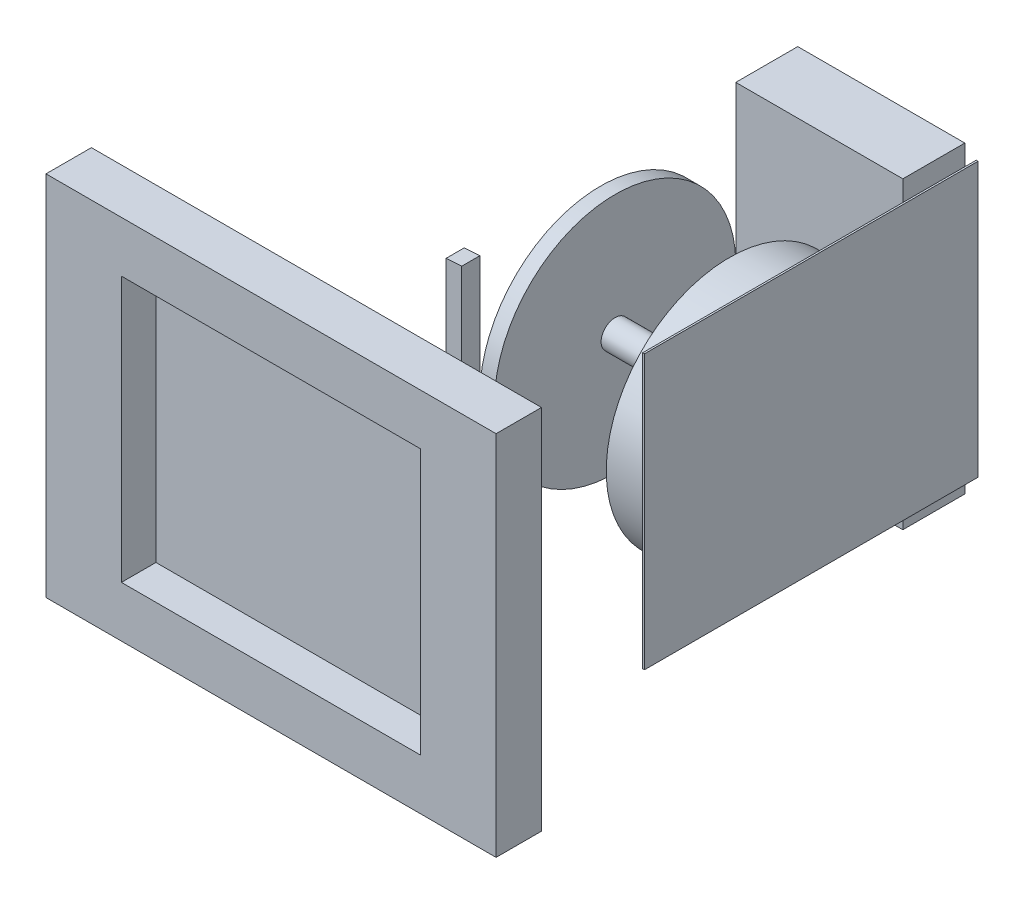
SolidWorks part; units mm, degrees
ref_plane "前视基准面" through (0, 0, 0) normal (0, 0, 1) x (1, 0, 0)
ref_plane "上视基准面" through (0, 0, 0) normal (0, 1, 0) x (1, 0, 0)
ref_plane "右视基准面" through (0, 0, 0) normal (1, 0, 0) x (0, 0, -1)
sketch "草图1" plane through (0, 0, 0) normal (1, 0, 0) x (0, 0, -1)
  circle A0 centre (0, 0) radius 66.4633
extrude "凸台-拉伸1" add sketch "草图1" along normal blind 5
sketch "草图2" plane through (5, 0, 0) normal (1, 0, 0) x (0, 0, -1)
  circle A3 centre (0, 36) radius 4.5304
  circle A6 centre (0, 15) radius 3.9065
  circle A7 centre (0, 0) radius 5.4141
  circle A8 centre (0, 58.5926) radius 4
  circle A9 centre (14.5714, 56.7518) radius 4
  circle A10 centre (28.2272, 51.3451) radius 4
  circle A11 centre (40.1094, 42.7122) radius 4
  circle A12 centre (49.4714, 31.3955) radius 4
  circle A13 centre (55.7249, 18.1061) radius 4
  circle A14 centre (58.477, 3.6791) radius 4
  circle A15 centre (57.5548, -10.9792) radius 4
  circle A16 centre (53.0162, -24.9475) radius 4
  circle A17 centre (45.1464, -37.3483) radius 4
  circle A18 centre (34.4399, -47.4024) radius 4
  circle A19 centre (21.5694, -54.478) radius 4
  circle A20 centre (7.3436, -58.1306) radius 4
  circle A21 centre (-7.3436, -58.1306) radius 4
  circle A22 centre (-21.5694, -54.478) radius 4
  circle A23 centre (-34.4399, -47.4024) radius 4
  circle A24 centre (-45.1464, -37.3483) radius 4
  circle A25 centre (-53.0162, -24.9475) radius 4
  circle A26 centre (-57.5548, -10.9792) radius 4
  circle A27 centre (-58.477, 3.6791) radius 4
  circle A28 centre (-55.7249, 18.1061) radius 4
  circle A29 centre (-49.4714, 31.3955) radius 4
  circle A30 centre (-40.1094, 42.7122) radius 4
  circle A31 centre (-28.2272, 51.3451) radius 4
  circle A32 centre (-14.5714, 56.7518) radius 4
  circle A33 centre (0, 48) radius 4.1999
  circle A34 centre (14.8328, 45.6507) radius 4.1999
  circle A35 centre (28.2137, 38.8328) radius 4.1999
  circle A36 centre (38.8328, 28.2137) radius 4.1999
  circle A37 centre (45.6507, 14.8328) radius 4.1999
  circle A38 centre (48, 0) radius 4.1999
  circle A39 centre (45.6507, -14.8328) radius 4.1999
  circle A40 centre (38.8328, -28.2137) radius 4.1999
  circle A41 centre (28.2137, -38.8328) radius 4.1999
  circle A42 centre (14.8328, -45.6507) radius 4.1999
  circle A43 centre (0, -48) radius 4.1999
  circle A44 centre (-14.8328, -45.6507) radius 4.1999
  circle A45 centre (-28.2137, -38.8328) radius 4.1999
  circle A46 centre (-38.8328, -28.2137) radius 4.1999
  circle A47 centre (-45.6507, -14.8328) radius 4.1999
  circle A48 centre (-48, 0) radius 4.1999
  circle A49 centre (-45.6507, 14.8328) radius 4.1999
  circle A50 centre (-38.8328, 28.2137) radius 4.1999
  circle A51 centre (-28.2137, 38.8328) radius 4.1999
  circle A52 centre (-14.8328, 45.6507) radius 4.1999
  circle A53 centre (12.3127, 33.8289) radius 4.5304
  circle A54 centre (23.1404, 27.5776) radius 4.5304
  circle A55 centre (31.1769, 18) radius 4.5304
  circle A56 centre (35.4531, 6.2513) radius 4.5304
  circle A57 centre (35.4531, -6.2513) radius 4.5304
  circle A58 centre (31.1769, -18) radius 4.5304
  circle A59 centre (23.1404, -27.5776) radius 4.5304
  circle A60 centre (12.3127, -33.8289) radius 4.5304
  circle A61 centre (0, -36) radius 4.5304
  circle A62 centre (-12.3127, -33.8289) radius 4.5304
  circle A63 centre (-23.1404, -27.5776) radius 4.5304
  circle A64 centre (-31.1769, -18) radius 4.5304
  circle A65 centre (-35.4531, -6.2513) radius 4.5304
  circle A66 centre (-35.4531, 6.2513) radius 4.5304
  circle A67 centre (-31.1769, 18) radius 4.5304
  circle A68 centre (-23.1404, 27.5776) radius 4.5304
  circle A69 centre (-12.3127, 33.8289) radius 4.5304
  circle A70 centre (0, 25) radius 4.3126
  circle A71 centre (12.5, 21.6506) radius 4.3126
  circle A72 centre (21.6506, 12.5) radius 4.3126
  circle A73 centre (25, 0) radius 4.3126
  circle A74 centre (21.6506, -12.5) radius 4.3126
  circle A75 centre (12.5, -21.6506) radius 4.3126
  circle A76 centre (0, -25) radius 4.3126
  circle A77 centre (-12.5, -21.6506) radius 4.3126
  circle A78 centre (-21.6506, -12.5) radius 4.3126
  circle A79 centre (-25, 0) radius 4.3126
  circle A80 centre (-21.6506, 12.5) radius 4.3126
  circle A81 centre (-12.5, 21.6506) radius 4.3126
  circle A82 centre (10.6066, 10.6066) radius 3.9065
  circle A83 centre (15, 0) radius 3.9065
  circle A84 centre (10.6066, -10.6066) radius 3.9065
  circle A85 centre (0, -15) radius 3.9065
  circle A86 centre (-10.6066, -10.6066) radius 3.9065
  circle A87 centre (-15, 0) radius 3.9065
  circle A88 centre (-10.6066, 10.6066) radius 3.9065
  point P52 (0, 0)
  point P104 (0, 0)
  point P140 (0, 0)
  point P164 (0, 0)
  point P180 (0, 0)
  dimension "D2" = 20
  dimension "D3" = 18
  dimension "D4" = 12
  dimension "D5" = 8
  dimension "D1" = 25
extrude "切除-拉伸1" cut sketch "草图2" against normal blind 10
sketch "草图3" plane through (5, 0, 0) normal (1, 0, 0) x (0, 0, -1)
  circle A0 centre (0, 0) radius 5.4141
  circle A1 centre (0, 0) radius 7.7131
extrude "凸台-拉伸3" add sketch "草图3" along normal blind 24
sketch "草图4" plane through (29, 0, 0) normal (1, 0, 0) x (0, 0, -1)
  circle A0 centre (0, 0) radius 6.6011
extrude "凸台-拉伸4" add sketch "草图4" along normal blind 24
sketch "草图5" plane through (53, 0, 0) normal (1, 0, 0) x (0, 0, -1)
  circle A0 centre (0, 0) radius 5.3512
extrude "凸台-拉伸5" add sketch "草图5" along normal blind 24
sketch "草图6" plane through (77, 0, 0) normal (1, 0, 0) x (0, 0, -1)
  circle A0 centre (0, 0) radius 3.9079
extrude "凸台-拉伸6" add sketch "草图6" along normal blind 24
sketch "草图7" plane through (29, 0, 0) normal (-1, 0, 0) x (0, 0, 1)
  circle A0 centre (0, 0) radius 5.4141
extrude "凸台-拉伸7" add sketch "草图7" along normal up to surface (29 mm away) up to face at (0, 6.2513, 30.9226)
ref_plane "基准面1" through (0, 0, 66.4633) normal (0, 0, 1) x (1, 0, 0)
sketch "草图8" plane through (0, 0, 66.4633) normal (0, 0, 1) x (1, 0, 0)
  line L0 (0, -66.4633) -> (0, 66.4633)
  line L1 (0, 66.4633) -> (-8.6103, 65.9032)
  line L2 (-8.6103, 65.9032) -> (-8.6103, -65.9032)
  line L3 (-8.6103, -65.9032) -> (0, -66.4633)
extrude "凸台-拉伸8" add sketch "草图8" along normal blind 10 separate body
sketch "草图9" plane through (0, 0, 76.4633) normal (0, 0, 1) x (1, 0, 0)
  circle A0 centre (0, 0) radius 8.6103
extrude "凸台-拉伸9" add sketch "草图9" along normal blind 80
sketch "草图13" plane through (5, 0, 0) normal (1, 0, 0) x (0, 0, -1)
  circle A0 centre (0, 0) radius 66.4633
  circle A1 centre (0, 0) radius 7.7131
extrude "凸台-拉伸11" add sketch "草图13" along normal blind 3
sketch "草图15" plane through (101, 0, 0) normal (1, 0, 0) x (0, 0, -1)
  circle A0 centre (0, 0) radius 66.4633
  circle A1 centre (0, 0) radius 67.8819
extrude "凸台-拉伸12" add sketch "草图15" against normal blind 30 separate body
sketch "草图16" plane through (101, 0, 0) normal (1, 0, 0) x (0, 0, -1)
  line L1 (-76.8392, 75.3514) -> (76.8392, 75.3514)
  line L2 (-76.8392, 75.3514) -> (-76.8392, -75.3514)
  line L3 (-76.8392, -75.3514) -> (76.8392, -75.3514)
  line L4 (76.8392, 75.3514) -> (76.8392, -75.3514)
  line L5 (-76.8392, 75.3514) -> (76.8392, -75.3514) construction
  line L6 (-76.8392, -75.3514) -> (76.8392, 75.3514) construction
  point P0 (0, 0)
extrude "凸台-拉伸13" add sketch "草图16" against normal blind 1
sketch "草图17" plane through (101, 0, 0) normal (1, 0, 0) x (0, 0, -1)
  circle A0 centre (0, 0) radius 148.288
ref_plane "基准面3" through (0, 0, -66.4567) normal (0, 0, -1) x (-1, 0, 0)
sketch "草图19" plane through (0, 0, -66.4567) normal (0, 0, -1) x (-1, 0, 0)
  line L0 (-8, 66.4633) -> (-21.6479, 66.4633)
  line L2 (-8, -66.4633) -> (-8, 66.4633)
  line L3 (-21.6479, 66.4633) -> (-21.6479, -66.4633)
  line L4 (-21.6479, -66.4633) -> (-8, -66.4633)
  point P6 (0, 0)
sketch "草图20" plane through (8, 0, 0) normal (1, 0, 0) x (0, 0, -1)
  line L0 (66.4567, -66.4633) -> (66.4567, 66.4633)
  line L1 (66.4567, 66.4633) -> (66.4567, -66.4633) construction
  line L2 (66.4567, 66.4633) -> (97.9084, 66.4633)
  line L3 (97.9084, 66.4633) -> (97.9084, -66.4633)
  line L4 (97.9084, -66.4633) -> (66.4567, -66.4633)
  line L5 (66.4567, 66.4633) -> (66.4567, -66.4633)
  line L6 (66.4567, -66.4633) -> (66.4567, -80.7109)
  line L7 (66.4567, -80.7109) -> (100.5838, -80.7109)
  line L8 (100.5838, -80.7109) -> (100.5838, 86.6618)
  line L9 (100.5838, 86.6618) -> (66.4567, 86.6618)
  line L10 (66.4567, 86.6618) -> (66.4567, 66.4633)
extrude "凸台-拉伸14" add sketch "草图20" along normal up to surface (92 mm away) separate body contours L9 L10 L2 L3 L4 L6 L7 L8 up to face at (100, 0, -67.8819)
sketch "草图22" plane through (0, 0, -76.8392) normal (0, 0, -1) x (-1, 0, 0)
  line L0 (-101, -75.3514) -> (-100, -75.3514)
  line L1 (-100, -75.3514) -> (-100, 75.3514)
  line L2 (-100, 75.3514) -> (-101, 75.3514)
  line L3 (-101, 75.3514) -> (-101, -75.3514)
extrude "凸台-拉伸17" add sketch "草图22" along normal blind 30
sketch "草图23" plane through (0, 0, -66.4567) normal (0, 0, 1) x (1, 0, 0)
  line L0 (8, 66.4633) -> (8, -66.4633)
  line L1 (8, -66.4633) -> (100, -67.8819)
  line L2 (100, -67.8819) -> (100, 67.8819)
  line L3 (100, 67.8819) -> (8, 66.4633)
extrude "凸台-拉伸18" add sketch "草图23" against normal blind 2
sketch "草图24" plane through (8, 0, 0) normal (-1, 0, 0) x (0, 0, 1)
  line L0 (-100.5838, -80.7109) -> (-66.4567, -80.7109)
  line L1 (-66.4567, -80.7109) -> (-66.4567, -75.3514)
  line L2 (-66.4567, -13.8369) -> (-66.4567, -75.3514) construction
  line L3 (-66.4567, -0.938) -> (-66.4567, -80.7109) construction
  line L4 (-66.4567, -75.3514) -> (-100.5838, -75.3514)
  line L5 (-100.5838, 75.3514) -> (-100.5838, -75.3514) construction
  line L6 (-100.5838, -80.7109) -> (-100.5838, 86.6618) construction
  line L7 (-100.5838, -75.3514) -> (-100.5838, -80.7109)
extrude "凸台-拉伸19" add sketch "草图24" along normal blind 114
sketch "草图25" plane through (0, 0, 156.4633) normal (0, 0, 1) x (1, 0, 0)
  line L1 (-123.9167, 101.0385) -> (123.9167, 101.0385)
  line L2 (-123.9167, 101.0385) -> (-123.9167, -101.0385)
  line L3 (-123.9167, -101.0385) -> (123.9167, -101.0385)
  line L4 (123.9167, 101.0385) -> (123.9167, -101.0385)
  line L5 (-123.9167, 101.0385) -> (123.9167, -101.0385) construction
  line L6 (-123.9167, -101.0385) -> (123.9167, 101.0385) construction
  point P0 (0, 0)
extrude "凸台-拉伸20" add sketch "草图25" along normal blind 25
sketch "草图26" plane through (0, 0, 181.4633) normal (0, 0, 1) x (1, 0, 0)
  line L1 (-82.3799, 73.03) -> (82.3799, 73.03)
  line L2 (-82.3799, 73.03) -> (-82.3799, -73.03)
  line L3 (-82.3799, -73.03) -> (82.3799, -73.03)
  line L4 (82.3799, 73.03) -> (82.3799, -73.03)
  line L5 (-82.3799, 73.03) -> (82.3799, -73.03) construction
  line L6 (-82.3799, -73.03) -> (82.3799, 73.03) construction
  point P0 (0, 0)
extrude "切除-拉伸3" cut sketch "草图26" against normal blind 19
sketch "草图27" plane through (0, 0, 162.4633) normal (0, 0, 1) x (1, 0, 0)
  circle A0 centre (0, 0) radius 9.4043
